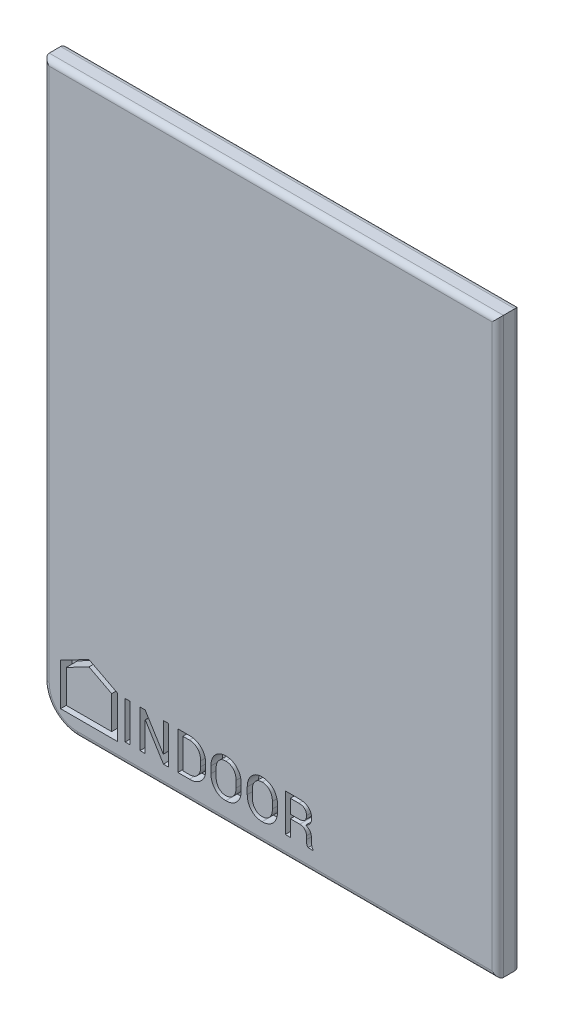
SolidWorks part; units mm, degrees
ref_plane "Front Plane" through (0, 0, 0) normal (0, 0, 1) x (1, 0, 0)
ref_plane "Top Plane" through (0, 0, 0) normal (0, 1, 0) x (1, 0, 0)
ref_plane "Right Plane" through (0, 0, 0) normal (1, 0, 0) x (0, 0, -1)
sketch "Sketch1" plane through (0, 0, 0) normal (0, 0, 1) x (1, 0, 0)
  line L1 (-20, 5.5) -> (-20, -42) construction
  line L6 (-15, -37.5) -> (-12, -37.5)
  line L7 (-15, -37.5) -> (-15, -34.5)
  line L8 (-15, -34.5) -> (-12, -34.5)
  line L9 (-12, -37.5) -> (-12, -34.5)
  line L14 (-17.5, -44.5) -> (19.5, -44.5) construction
  line L16 (-0.25, 5.5) -> (0, -44.5) construction
  line L17 (-20, 5.5) -> (19.5, 5.5) construction
  line L18 (-19.75, -19.5) -> (19.5, -19.5) construction
  line L19 (19.5, 5.5) -> (19.5, -44.5) construction
  line L20 (-15, -4.5) -> (-12, -4.5)
  line L21 (-12, -1.5) -> (-12, -4.5)
  line L22 (-15, -1.5) -> (-12, -1.5)
  line L23 (-15, -1.5) -> (-15, -4.5)
  line L24 (14.8993, -34.3505) -> (11.8994, -34.3805)
  line L25 (11.9294, -37.3804) -> (11.8994, -34.3805)
  line L26 (14.9293, -37.3504) -> (11.9294, -37.3804)
  line L27 (14.9293, -37.3504) -> (14.8993, -34.3505)
  line L28 (14.5693, -1.3522) -> (14.5993, -4.352)
  line L29 (14.5693, -1.3522) -> (11.5694, -1.3822)
  line L30 (11.5694, -1.3822) -> (11.5994, -4.382)
  line L31 (14.5993, -4.352) -> (11.5994, -4.382)
  point P14 (-0.125, -19.5)
  dimension "D1" = 5
  dimension "D2" = 7
  dimension "D3" = 3
extrude "Boss-Extrude1" add sketch "Sketch1" along normal blind 4
sketch "Sketch2" plane through (0, 0, 4) normal (0, 0, 1) x (1, 0, 0)
  line L0 (-20.5, -42) -> (-20.5, 5.5) construction
  line L1 (-20.5, -42) -> (-20.5, 5.5)
  line L2 (19.5, -45) -> (-17.5, -45) construction
  line L3 (19.5, -45) -> (-17.5, -45)
  line L4 (19.5, 5.5) -> (19.5, -44.5) construction
  line L5 (19.5, 5.5) -> (19.5, -45)
  line L6 (-20, 5.5) -> (19.5, 5.5) construction
  line L7 (-20.5, 5.5) -> (19.5, 5.5)
  arc A0 (-20.5, -42) -> (-17.5, -45) centre (-17.5, -42) ccw construction
  arc A1 (-20.5, -42) -> (-17.5, -45) centre (-17.5, -42) ccw
extrude "Boss-Extrude2" add sketch "Sketch2" along normal blind 2
fillet "Fillet1" radius 0.5 10 edges at (1, -45, 6) (-19.6213, -44.1213, 6) (1, -45, 4) (-19.6213, -44.1213, 4) (19.5, -19.75, 4) (19.5, -19.75, 6) (-0.5, 5.5, 6) (-20.5, -18.25, 6) (-0.5, 5.5, 4) (-20.5, -18.25, 4)
sketch "Sketch3" plane through (0, 0, 6) normal (0, 0, 1) x (1, 0, 0)
  line L0 (-13.75, -43.2) -> (3.4554, -43.2) construction
  line L1 (-13.75, -43.2) -> (3.4554, -43.2) construction
  line L5 (-18.5, -40.1036) -> (-18.5, -43)
  line L6 (-18.5, -43) -> (-14.5, -43)
  line L7 (-14.5, -43) -> (-14.5, -40.1036)
  line L8 (-14.5, -40.1036) -> (-16.5, -39.0636)
  line L9 (-16.5, -39.0636) -> (-18.5, -40.1036)
  line L10 (-18.5, -40.1036) -> (-18.5, -43)
  line L11 (-18.5, -43) -> (-14.5, -43)
  line L12 (-14.5, -43) -> (-14.5, -40.1036)
  line L13 (-14.5, -40.1036) -> (-16.5, -39.0636)
  line L14 (-16.5, -39.0636) -> (-18.5, -40.1036)
  line L15 (-19, -43.5) -> (-14, -43.5)
  line L16 (-19, -39.8) -> (-19, -43.5)
  line L17 (-16.5, -38.5) -> (-19, -39.8)
  line L18 (-14, -39.8) -> (-16.5, -38.5)
  line L19 (-14, -43.5) -> (-14, -39.8)
  line L20 (-19, -43.5) -> (-14, -43.5)
  line L21 (-19, -39.8) -> (-19, -43.5)
  line L22 (-16.5, -38.5) -> (-19, -39.8)
  line L23 (-14, -39.8) -> (-16.5, -38.5)
  line L24 (-14, -43.5) -> (-14, -39.8)
  text T0 "INDOOR" font "Roboto" height in points 9
  dimension "D1" = 0
  dimension "D2" = 0
extrude "Cut-Extrude1" cut sketch "Sketch3" against normal blind 1
